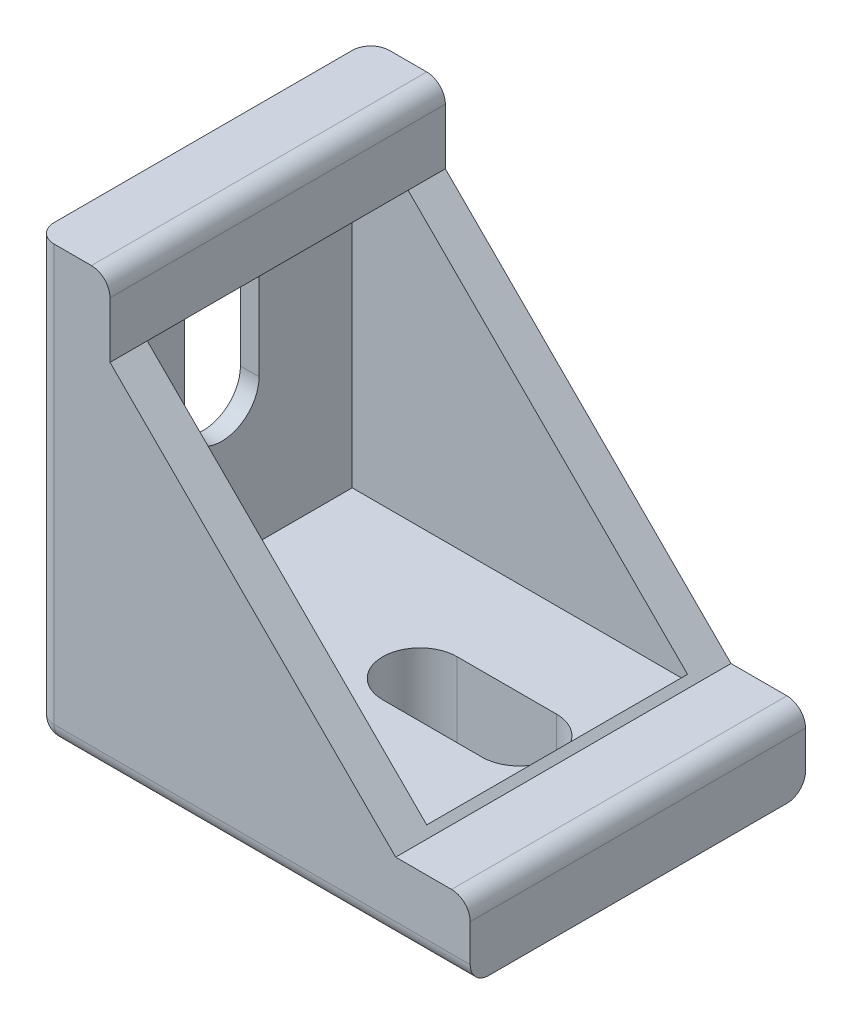
SolidWorks part; units mm, degrees
ref_plane "前视" through (0, 0, 0) normal (0, 0, 1) x (1, 0, 0)
ref_plane "上视" through (0, 0, 0) normal (0, 1, 0) x (1, 0, 0)
ref_plane "右视" through (0, 0, 0) normal (1, 0, 0) x (0, 0, -1)
sketch "草图1" plane through (0, 0, 0) normal (0, 0, 1) x (1, 0, 0)
  line L0 (-11.5, 11.5) -> (11.5, -11.5)
  line L1 (-17.5, 17.5) -> (-11.5, 17.5)
  line L2 (-17.5, 17.5) -> (-17.5, -17.5)
  line L3 (-17.5, -17.5) -> (17.5, -17.5)
  line L5 (-17.5, 17.5) -> (17.5, -17.5) construction
  line L6 (-17.5, -17.5) -> (17.5, 17.5) construction
  line L8 (-11.5, 17.5) -> (-11.5, 11.5)
  line L10 (17.5, -17.5) -> (17.5, -11.5)
  line L11 (17.5, -11.5) -> (11.5, -11.5)
  point P0 (0, 0)
  dimension "D1" = 35
  dimension "D2" = 35
  dimension "D3" = 6
  dimension "D4" = 6
  dimension "D5" = 6
  dimension "D6" = 6
extrude "凸台-拉伸1" add sketch "草图1" along normal blind 27
fillet "圆角1" radius 1.5 2 edges at (17.5, -11.5, 13.5) (-11.5, 17.5, 13.5)
fillet "圆角2" radius 1.5 5 edges at (0, -17.5, 0) (-17.5, 0, 0) (-17.5, -17.5, 13.5) (0, -17.5, 27) (-17.5, 0, 27)
sketch "草图2" plane through (0, -17.5, 0) normal (0, -1, 0) x (1, 0, 0)
  line L0 (0, 13.5507) -> (8, 13.5507) construction
  line L1 (0, 16.5507) -> (8, 16.5507)
  line L2 (0, 10.5507) -> (8, 10.5507)
  arc A0 (0, 16.5507) -> (0, 10.5507) centre (0, 13.5507) ccw
  arc A1 (8, 10.5507) -> (8, 16.5507) centre (8, 13.5507) ccw
  point P2 (4, 13.5507)
  dimension "D2" = 3
  dimension "D1" = 8
extrude "切除-拉伸1" cut sketch "草图2" against normal blind 27
sketch "草图3" plane through (-17.5, 0, 0) normal (-1, 0, 0) x (0, 0, 1)
  line L0 (13.5, 0) -> (13.5, 8) construction
  line L1 (10.5, 0) -> (10.5, 8)
  line L2 (16.5, 0) -> (16.5, 8)
  arc A0 (10.5, 0) -> (16.5, 0) centre (13.5, 0) ccw
  arc A1 (16.5, 8) -> (10.5, 8) centre (13.5, 8) ccw
  point P2 (13.5, 4)
  dimension "D2" = 3
  dimension "D1" = 8
extrude "切除-拉伸2" cut sketch "草图3" against normal blind 27
ref_plane "基准面2" through (11, 0, 0) normal (1, 0, 0) x (0, 0, -1)
sketch "草图5" plane through (11, 0, 0) normal (1, 0, 0) x (0, 0, -1)
  line L0 (-27, -11.5) -> (0, -11.5) construction
  line L1 (-24, -11.5) -> (-3, -11.5)
  line L2 (-24, -11.5) -> (-24, 11.5)
  line L3 (-24, 11.5) -> (-3, 11.5)
  line L4 (-3, -11.5) -> (-3, 11.5)
  line L5 (-27, -11.5) -> (-27, 11.5) construction
  line L6 (0, -11.5) -> (0, 11.5) construction
  dimension "D1" = 3
  dimension "D2" = 3
  dimension "D3" = 23
extrude "切除-拉伸3" cut sketch "草图5" against normal blind 27
